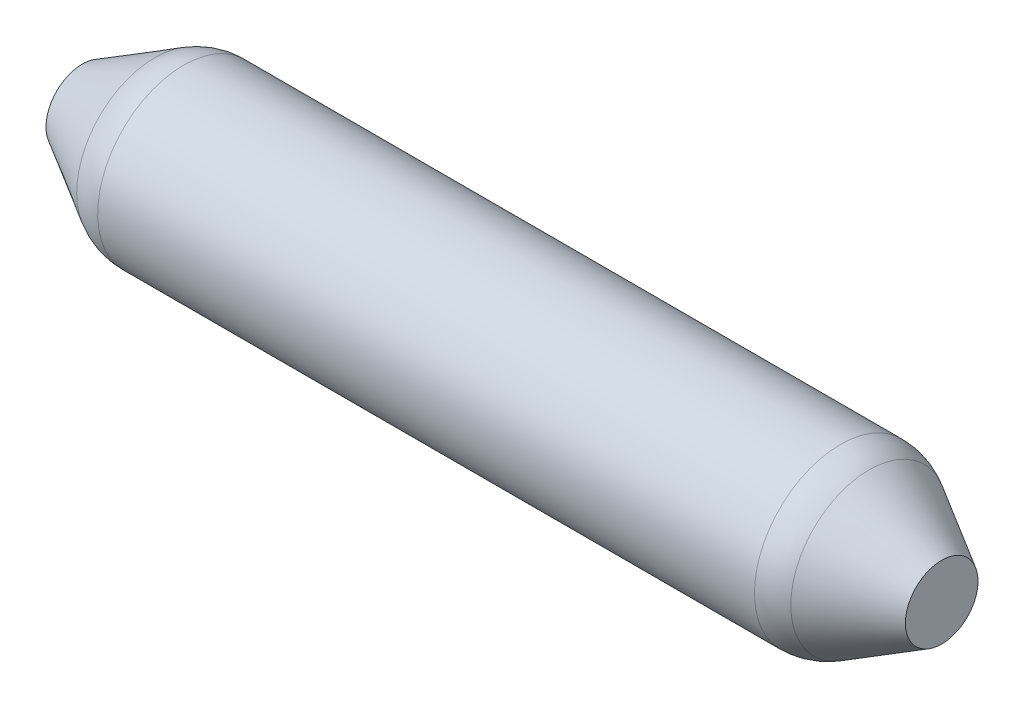
SolidWorks part; units mm, degrees
ref_plane "Ebene vorne" through (0, 0, 0) normal (0, 0, 1) x (1, 0, 0)
ref_plane "Ebene oben" through (0, 0, 0) normal (0, 1, 0) x (1, 0, 0)
ref_plane "Ebene rechts" through (0, 0, 0) normal (1, 0, 0) x (0, 0, -1)
sketch "Skizze1" plane through (0, 0, 0) normal (0, 0, 1) x (1, 0, 0)
  line L0 (0, 0) -> (30, 0) construction
  line L1 (0, 0) -> (0, 1.2679)
  line L2 (0, 1.2679) -> (3, 3)
  line L3 (3, 3) -> (27, 3)
  line L4 (15, 3) -> (15, 0) construction
  line L5 (30, 0) -> (30, 1.2679)
  line L6 (30, 1.2679) -> (27, 3)
  line L7 (0, 0) -> (30, 0)
  dimension "Durchmesser" = 6
  dimension "Laenge" = 30
  dimension "D3" = 120
  dimension "D4" = 3
revolve "Rotation1" add sketch "Skizze1" angle 360 about L7
fillet "Verrundung1" radius 2 2 edges at (3, -3, 0) (27, -3, 0)
equation "\"D4@Skizze1\" = \"Laenge@Skizze1\" / 10"
